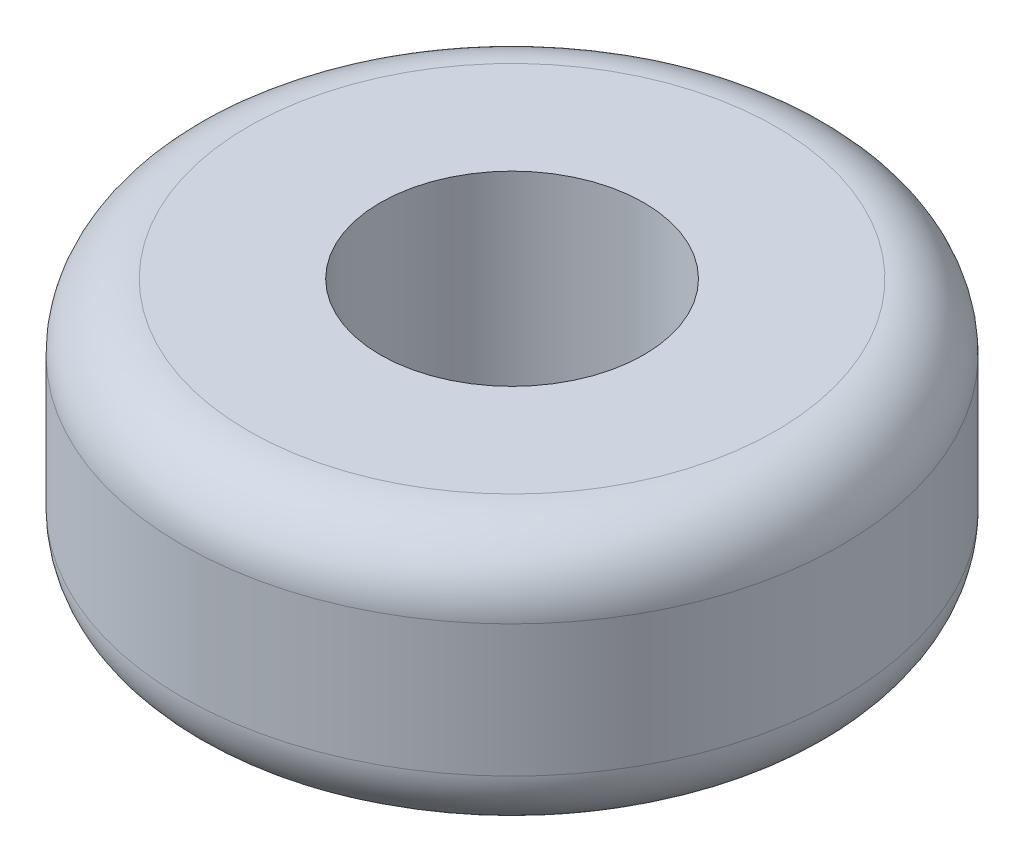
SolidWorks part; units mm, degrees
ref_plane "Front Plane" through (0, 0, 0) normal (0, 0, 1) x (1, 0, 0)
ref_plane "Top Plane" through (0, 0, 0) normal (0, 1, 0) x (1, 0, 0)
ref_plane "Right Plane" through (0, 0, 0) normal (1, 0, 0) x (0, 0, -1)
sketch "Sketch1" plane through (0, 0, 0) normal (0, 1, 0) x (1, 0, 0)
  circle A0 centre (0, 0) radius 31.75
extrude "Boss-Extrude1" add sketch "Sketch1" along normal blind 25.4
sketch "Sketch2" plane through (0, 25.4, 0) normal (0, 1, 0) x (1, 0, 0)
  circle A0 centre (0, 0) radius 12.7
extrude "Cut-Extrude1" cut sketch "Sketch2" against normal through all
fillet "Fillet1" radius 6.35 2 edges at (0, 0, 31.75) (0, 25.4, 31.75)
